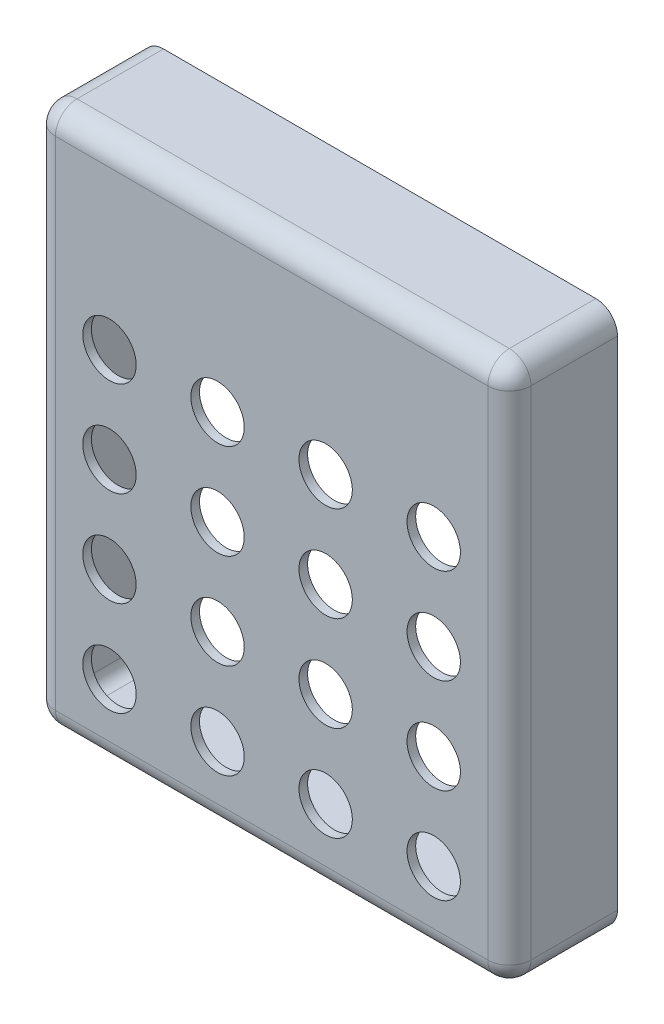
SolidWorks part; units mm, degrees
ref_plane "Front Plane" through (0, 0, 0) normal (0, 0, 1) x (1, 0, 0)
ref_plane "Top Plane" through (0, 0, 0) normal (0, 1, 0) x (1, 0, 0)
ref_plane "Right Plane" through (0, 0, 0) normal (1, 0, 0) x (0, 0, -1)
sketch "Sketch1" plane through (0, 0, 0) normal (0, 0, 1) x (1, 0, 0)
  line L1 (-50, -62.5) -> (50, -62.5)
  line L2 (-55, -57.5) -> (-55, 57.5)
  line L3 (-50, 62.5) -> (50, 62.5)
  line L4 (55, -57.5) -> (55, 57.5)
  line L5 (-55, -62.5) -> (55, 62.5) construction
  line L6 (-55, 62.5) -> (55, -62.5) construction
  arc A0 (-50, -62.5) -> (-55, -57.5) centre (-50, -57.5) cw
  arc A1 (50, -62.5) -> (55, -57.5) centre (50, -57.5) ccw
  arc A2 (50, 62.5) -> (55, 57.5) centre (50, 57.5) cw
  arc A3 (-55, 57.5) -> (-50, 62.5) centre (-50, 57.5) cw
  point P0 (0, 0)
  dimension "D3" = 5
  dimension "D1" = 110
  dimension "D2" = 125
extrude "Boss-Extrude1" add sketch "Sketch1" along normal blind 25
fillet "Fillet1" radius 5 8 edges at (-55, 0, 25) (-53.5355, 61.0355, 25) (0, 62.5, 25) (53.5355, 61.0355, 25) (55, 0, 25) (53.5355, -61.0355, 25) (0, -62.5, 25) (-53.5355, -61.0355, 25)
shell "Shell1" thickness 2
sketch "Sketch2" plane through (0, 0, 25) normal (0, 0, 1) x (1, 0, 0)
  line L0 (0, -57.5) -> (0, -32.5) construction
  line L1 (-50, -57.5) -> (50, -57.5) construction
  line L2 (50, -45) -> (-50, -45) construction
  line L3 (50, -57.5) -> (50, 57.5) construction
  line L4 (-50, 57.5) -> (-50, -57.5) construction
  line L5 (-25, -45) -> (-50, -45) construction
  line L6 (-25, -45) -> (-50, -45) construction
  line L7 (-50, -45) -> (-37.5, -45) construction
  circle A0 centre (-37.5, -45) radius 6.175
  circle A1 centre (-12.5, -45) radius 6.175
  circle A2 centre (12.5, -45) radius 6.175
  circle A3 centre (37.5, -45) radius 6.175
  circle A4 centre (-37.5, -23) radius 6.175
  circle A5 centre (-12.5, -23) radius 6.175
  circle A6 centre (12.5, -23) radius 6.175
  circle A7 centre (37.5, -23) radius 6.175
  circle A8 centre (-37.5, -1) radius 6.175
  circle A9 centre (-12.5, -1) radius 6.175
  circle A10 centre (12.5, -1) radius 6.175
  circle A11 centre (37.5, -1) radius 6.175
  circle A12 centre (-37.5, 21) radius 6.175
  circle A13 centre (-12.5, 21) radius 6.175
  circle A14 centre (12.5, 21) radius 6.175
  circle A15 centre (37.5, 21) radius 6.175
  dimension "D3" = 12.35
  dimension "D1" = 25
  dimension "D2" = 25
  dimension "D4" = 4
  dimension "D5" = 4
extrude "Cut-Extrude2" cut sketch "Sketch2" against normal blind 25
sketch "Sketch3" plane through (-55, 0, 0) normal (-1, 0, 0) x (0, 0, 1)
  line L0 (0, 57.5) -> (0, 35.5) construction
  line L1 (0, 57.5) -> (0, -57.5) construction
  line L2 (0, 46.5) -> (15.6813, 46.5) construction
  line L3 (14.1813, 46.5) -> (14.1813, 49.1) construction
  line L4 (14.1813, 42.5) -> (16.6813, 42.5)
  line L5 (14.1813, 42.5) -> (14.1813, 50.5)
  line L6 (14.1813, 50.5) -> (16.6813, 50.5)
  line L7 (17.1813, 43) -> (17.1813, 50)
  line L8 (14.1813, 42.5) -> (17.1813, 50.5) construction
  line L9 (14.1813, 50.5) -> (17.1813, 42.5) construction
  line L10 (16.6813, 50.5) -> (14.1813, 49.1)
  line L11 (14.1813, 49.1) -> (14.1813, 43.9)
  line L12 (16.6813, 42.5) -> (14.1813, 43.9)
  arc A0 (16.6813, 42.5) -> (17.1813, 43) centre (16.6813, 43) ccw
  arc A1 (16.6813, 50.5) -> (17.1813, 50) centre (16.6813, 50) cw
  dimension "D4" = 0.5
  dimension "D1" = 22
  dimension "D2" = 3
  dimension "D3" = 8
  dimension "D5" = 2.6
  dimension "D6" = 5.2
extrude "Cut-Extrude4" cut sketch "Sketch3" against normal blind 25 contours A1 L10 L5 L12 A0 L7
sketch "Sketch4" plane through (0, 0, 17.1813) normal (0, 0, -1) x (-1, 0, 0)
  line L0 (55, 46.4692) -> (53, 46.4692) construction
  line L1 (55, 57.5) -> (55, -57.5) construction
  line L2 (53, 57.5) -> (53, -57.5) construction
  line L3 (53, 46.4692) -> (2, 46.4692) construction
  line L4 (27.5, 46.4692) -> (27.5, 52.4692) construction
  line L5 (2, 35.9692) -> (53, 35.9692)
  line L6 (2, 35.9692) -> (2, 56.9692)
  line L7 (2, 56.9692) -> (53, 56.9692)
  line L8 (53, 35.9692) -> (53, 56.9692)
  line L9 (2, 35.9692) -> (53, 56.9692) construction
  line L10 (2, 56.9692) -> (53, 35.9692) construction
  line L11 (27.5, 52.4692) -> (50.75, 52.4692) construction
  circle A0 centre (50.75, 52.4692) radius 1.25
  circle A1 centre (50.75, 52.4692) radius 0.5
  circle A2 centre (4.25, 52.4692) radius 0.5
  circle A3 centre (4.25, 52.4692) radius 1.25
  circle A4 centre (4.25, 40.4692) radius 1.25
  circle A5 centre (4.25, 40.4692) radius 0.5
  circle A6 centre (50.75, 40.4692) radius 1.25
  circle A7 centre (50.75, 40.4692) radius 0.5
  point P6 (27.5, 46.4692)
  dimension "D5" = 2.5
  dimension "D6" = 1
  dimension "D1" = 51
  dimension "D2" = 21
  dimension "D3" = 23.25
  dimension "D4" = 6
extrude "Boss-Extrude2" add sketch "Sketch4" against normal blind 7 contours A6 A7 | A0 A1 | A3 A2 | A4 A5
sketch "Sketch5" plane through (0, 0, 17.1813) normal (0, 0, -1) x (-1, 0, 0)
  line L1 (52.2588, 38.321) -> (1.2884, 38.321)
  line L2 (52.2588, 38.321) -> (52.2588, 54.3581)
  line L3 (52.2588, 54.3581) -> (1.2884, 54.3581)
  line L4 (1.2884, 38.321) -> (1.2884, 54.3581)
extrude "Cut-Extrude5" cut sketch "Sketch5" against normal blind 1.5
